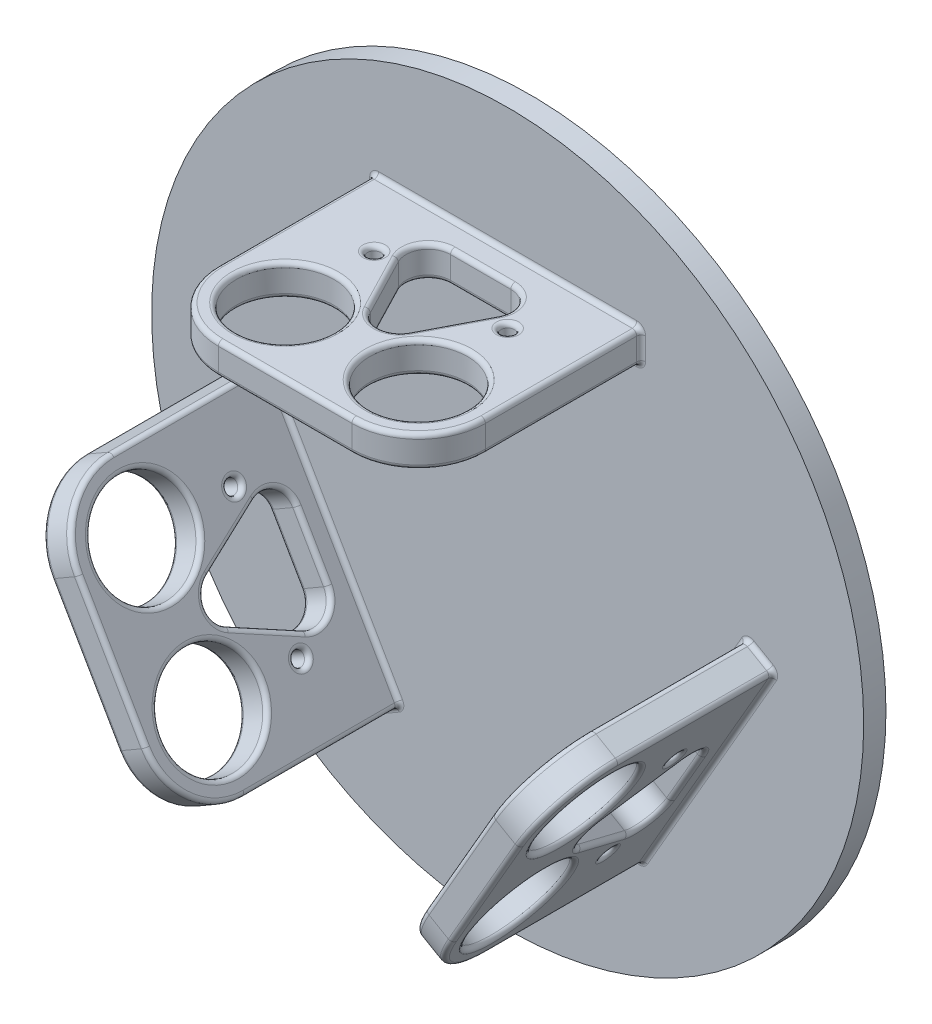
SolidWorks part; units mm, degrees
ref_plane "Plan de face" through (0, 0, 0) normal (0, 0, 1) x (1, 0, 0)
ref_plane "Plan de dessus" through (0, 0, 0) normal (0, 1, 0) x (1, 0, 0)
ref_plane "Plan de droite" through (0, 0, 0) normal (1, 0, 0) x (0, 0, -1)
sketch "Esquisse1" plane through (0, 0, 0) normal (0, 0, 1) x (1, 0, 0)
  circle A0 centre (0, 0) radius 80
  dimension "D1" = 160
extrude "Extrusion1" add sketch "Esquisse1" along normal blind 5
sketch "Esquisse4" plane through (0, 0, 5) normal (0, 0, 1) x (1, 0, 0)
  line L0 (-77.9423, 45) -> (0, -90) construction
  line L1 (0, -90) -> (77.9423, 45) construction
  line L2 (77.9423, 45) -> (-77.9423, 45) construction
  line L3 (0, 0) -> (0, -83.0117) construction
  line L4 (-77.9423, 45) -> (-84.0045, 41.5) construction
  line L5 (-84.0045, 41.5) -> (-6.0622, -93.5) construction
  line L6 (-6.0622, -93.5) -> (0, -90) construction
  line L7 (-77.9423, 52) -> (77.9423, 52) construction
  line L8 (77.9423, 52) -> (77.9423, 45) construction
  line L9 (-77.9423, 52) -> (-77.9423, 45) construction
  line L10 (6.0622, -93.5) -> (84.0045, 41.5) construction
  line L11 (84.0045, 41.5) -> (77.9423, 45) construction
  line L12 (6.0622, -93.5) -> (0, -90) construction
  line L13 (-60.0333, -0.0192) -> (-53.9711, 3.4808)
  line L14 (-30.0333, -51.9808) -> (-23.9711, -48.4808)
  line L15 (-84.0045, 41.5) -> (-53.9711, 3.4808) construction
  line L16 (-6.0622, -93.5) -> (-23.9711, -48.4808) construction
  line L17 (-60.0333, -0.0192) -> (-30.0333, -51.9808)
  line L18 (-23.9711, -48.4808) -> (-53.9711, 3.4808)
  line L19 (-30, 52) -> (30, 52)
  line L20 (30, 52) -> (30, 45)
  line L21 (30, 45) -> (-30, 45)
  line L22 (-30, 45) -> (-30, 52)
  line L23 (53.9711, 3.4808) -> (60.0333, -0.0192)
  line L24 (60.0333, -0.0192) -> (30.0333, -51.9808)
  line L25 (30.0333, -51.9808) -> (23.9711, -48.4808)
  line L26 (23.9711, -48.4808) -> (53.9711, 3.4808)
  line L29 (-30, 45) -> (-77.9423, 52) construction
  line L30 (77.9423, 45) -> (30, 52) construction
  line L31 (53.9711, 3.4808) -> (84.0045, 41.5) construction
  line L32 (23.9711, -48.4808) -> (6.0622, -93.5) construction
  circle A1 centre (0, 0) radius 90 construction
  dimension "D4" = 180
  dimension "D1" = 7
  dimension "D5" = 60
extrude "Extrusion2" add sketch "Esquisse4" along normal blind 50
sketch "Esquisse5" plane through (-45.0333, -26, 0) normal (-0.866, -0.5, 0) x (0, 0, 1)
  line L0 (40, 15) -> (40, -15) construction
  line L1 (0, 0) -> (40, 0) construction
  line L3 (40, 15) -> (20, 15) construction
  line L4 (55, 30) -> (55, -30) construction
  line L5 (20, 15) -> (20, -15) construction
  line L6 (20, -15) -> (40, -15) construction
  line L7 (31.0557, 4.4721) -> (17.2361, 11.382)
  line L8 (10, 6.9098) -> (10, -6.9098)
  line L9 (17.2361, -11.382) -> (31.0557, -4.4721)
  line L10 (20, 15) -> (10, 15) construction
  line L11 (20, -15) -> (10, -15) construction
  circle A0 centre (40, 15) radius 11
  circle A1 centre (40, -15) radius 11
  circle A4 centre (20, 15) radius 1.5
  circle A5 centre (20, -15) radius 1.5
  arc A6 (10, 6.9098) -> (17.2361, 11.382) centre (15, 6.9098) cw
  arc A7 (10, -6.9098) -> (17.2361, -11.382) centre (15, -6.9098) ccw
  arc A8 (31.0557, -4.4721) -> (31.0557, 4.4721) centre (28.8197, 0) ccw
  dimension "D1" = 22
  dimension "D7" = 3
  dimension "D9" = 5
  dimension "D2" = 15
  dimension "D3" = 30
  dimension "D6" = 20
  dimension "D8" = 10
extrude "Extrusion3" cut sketch "Esquisse5" against normal up to next
sketch "Esquisse6" plane through (45.0333, -26, 0) normal (0.866, -0.5, 0) x (0, 0, -1)
  line L0 (-40, 15) -> (-40, -15) construction
  line L1 (0, 0) -> (-40, 0) construction
  line L2 (-55, -30) -> (-55, 30) construction
  line L3 (-40, 15) -> (-20, 15) construction
  line L4 (-20, 15) -> (-20, -15) construction
  line L5 (-20, -15) -> (-40, -15) construction
  line L6 (-20, -15) -> (-10, -15) construction
  line L7 (-20, 15) -> (-10, 15) construction
  line L8 (-10, 6.9098) -> (-10, -6.9098)
  line L9 (-17.2361, -11.382) -> (-31.0557, -4.4721)
  line L10 (-31.0557, 4.4721) -> (-17.2361, 11.382)
  circle A0 centre (-40, 15) radius 11
  circle A1 centre (-40, -15) radius 11
  circle A2 centre (-20, 15) radius 1.5
  circle A3 centre (-20, -15) radius 1.5
  arc A4 (-31.0557, -4.4721) -> (-31.0557, 4.4721) centre (-28.8197, 0) cw
  arc A5 (-17.2361, 11.382) -> (-10, 6.9098) centre (-15, 6.9098) cw
  arc A6 (-10, -6.9098) -> (-17.2361, -11.382) centre (-15, -6.9098) cw
  dimension "D1" = 22
  dimension "D4" = 20
  dimension "D5" = 3
  dimension "D6" = 5
  dimension "D2" = 30
  dimension "D3" = 15
  dimension "D7" = 10
extrude "Extrusion4" cut sketch "Esquisse6" against normal up to next
sketch "Esquisse7" plane through (0, 52, 0) normal (0, 1, 0) x (1, 0, 0)
  line L0 (-15, -40) -> (15, -40) construction
  line L1 (0, 0) -> (0, -40) construction
  line L2 (30, -55) -> (-30, -55) construction
  line L4 (-15, -40) -> (-15, -20) construction
  line L5 (-15, -20) -> (15, -20) construction
  line L6 (15, -20) -> (15, -40) construction
  line L7 (15, -20) -> (15, -11.067) construction
  line L8 (6.7758, -11.067) -> (-6.7758, -11.067)
  line L9 (-11.2147, -18.3683) -> (-4.4389, -31.4379)
  line L10 (4.4389, -31.4379) -> (11.2147, -18.3683)
  line L11 (-15, -20) -> (-15, -11.067) construction
  circle A0 centre (-15, -40) radius 11
  circle A1 centre (15, -40) radius 11
  arc A2 (-11.2147, -18.3683) -> (-6.7758, -11.067) centre (-6.7758, -16.067) cw
  arc A3 (-4.4389, -31.4379) -> (4.4389, -31.4379) centre (0, -29.1366) ccw
  arc A4 (6.7758, -11.067) -> (11.2147, -18.3683) centre (6.7758, -16.067) cw
  circle A5 centre (-15, -20) radius 1.5
  circle A6 centre (15, -20) radius 1.5
  dimension "D2" = 22
  dimension "D4" = 5
  dimension "D5" = 3
  dimension "D1" = 30
  dimension "D3" = 15
  dimension "D6" = 20
extrude "Extrusion5" cut sketch "Esquisse7" against normal up to next
fillet "Congé1" radius 15 6 edges at (27.0022, -50.2308, 55) (57.0022, 1.7308, 55) (-27.0022, -50.2308, 55) (-57.0022, 1.7308, 55) (-30, 48.5, 55) (30, 48.5, 55)
fillet "Congé2" radius 1 102 edges at (30, 48.5, 5) (-30, 48.5, 5) (57.0022, 1.7308, 5) (27.0022, -50.2308, 5) (-57.0022, 1.7308, 5) (-27.0022, -50.2308, 5) (57.8366, -3.824, 50.6066) (60.0333, -0.0192, 22.5) (45.0333, -26, 5) (30.0333, -51.9808, 22.5) (32.23, -48.176, 50.6066) (45.0333, -26, 55) (58.0333, -3.4833, 40) (43.0333, -29.4641, 40) (38.2833, -37.6913, 20) (-51.7744, -0.324, 50.6066) (-53.9711, 3.4808, 22.5) (-38.9711, -22.5, 5) (-23.9711, -48.4808, 22.5) (-26.1678, -44.676, 50.6066) (-38.9711, -22.5, 55) (-40.9711, -19.0359, 40) (-25.9711, -45.0167, 40) (0, 52, 5) (30, 52, 22.5) (25.6066, 52, 50.6066) (0, 52, 55) (-25.6066, 52, 50.6066) (-30, 52, 22.5) (-15, 52, 51) (15, 52, 51) (25.6066, 45, 50.6066) (30, 45, 22.5) (0, 45, 5) (-30, 45, 22.5) (-25.6066, 45, 50.6066) (0, 45, 55) (-15, 45, 51) (15, 45, 51) (38.9711, -22.5, 5) (53.9711, 3.4808, 22.5) (51.7744, -0.324, 50.6066) (38.9711, -22.5, 55) (26.1678, -44.676, 50.6066) (23.9711, -48.4808, 22.5) (51.9711, 0.0167, 40) (36.9711, -25.9641, 40) (32.2211, -34.1913, 20) (-45.0333, -26, 5) (-60.0333, -0.0192, 22.5) (-57.8366, -3.824, 50.6066) (-45.0333, -26, 55) (-32.23, -48.176, 50.6066) (-30.0333, -51.9808, 22.5) (-47.0333, -22.5359, 40) (-32.0333, -48.5167, 40) (-45.7211, -10.8087, 20) (-30.7211, -36.7894, 20) (-51.7833, -14.3087, 20) (-36.7833, -40.2894, 20) (-38.9711, -22.5, 33.8197) (-35.0076, -29.365, 24.1459) (-33.3896, -32.1675, 12.3713) (-38.9711, -22.5, 10) (-44.5527, -12.8325, 12.3713) (-42.9347, -15.635, 24.1459) (-39.4518, -35.6675, 12.3713) (-41.0698, -32.865, 24.1459) (-45.0333, -26, 33.8197) (-48.9968, -19.135, 24.1459) (-50.6149, -16.3325, 12.3713) (-45.0333, -26, 10) (53.2833, -11.7106, 20) (39.4518, -35.6675, 12.3713) (45.0333, -26, 10) (50.6149, -16.3325, 12.3713) (48.9968, -19.135, 24.1459) (45.0333, -26, 33.8197) (41.0698, -32.865, 24.1459) (47.2211, -8.2106, 20) (44.5527, -12.8325, 12.3713) (38.9711, -22.5, 10) (33.3896, -32.1675, 12.3713) (35.0076, -29.365, 24.1459) (38.9711, -22.5, 33.8197) (42.9347, -15.635, 24.1459) (0, 52, 34.1366) (7.8268, 52, 24.9031) (11.0482, 52, 13.4695) (0, 52, 11.067) (-11.0482, 52, 13.4695) (-7.8268, 52, 24.9031) (-15, 52, 21.5) (15, 52, 21.5) (11.0482, 45, 13.4695) (7.8268, 45, 24.9031) (0, 45, 34.1366) (-7.8268, 45, 24.9031) (-11.0482, 45, 13.4695) (0, 45, 11.067) (-15, 45, 21.5) (15, 45, 21.5)
